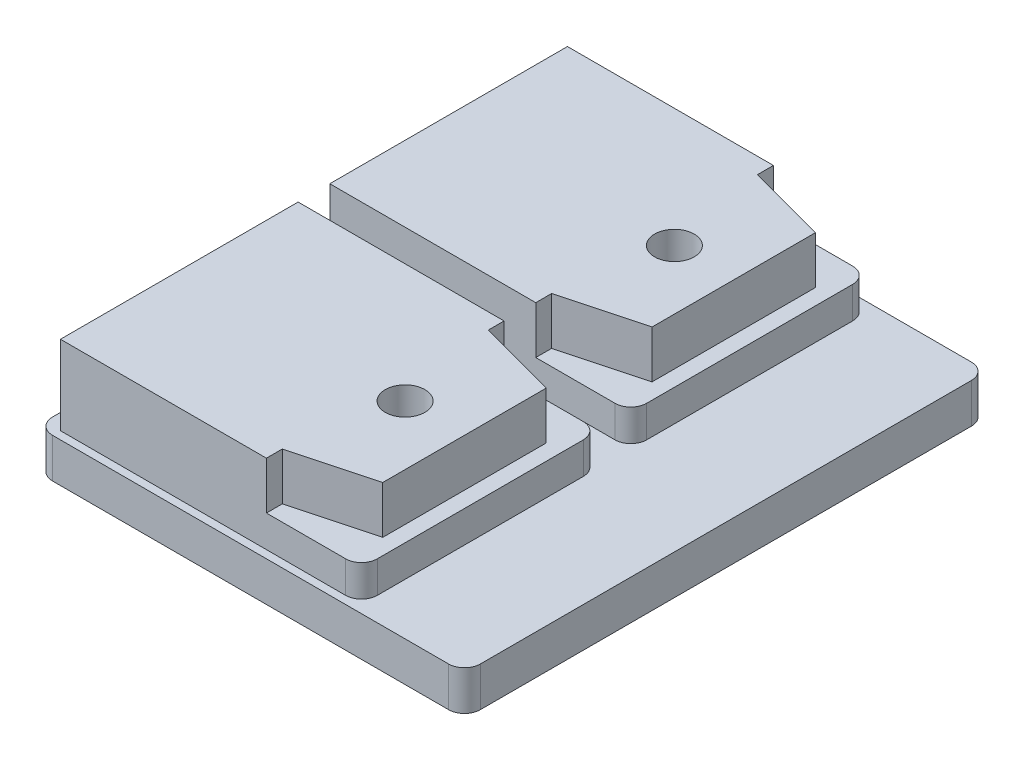
SolidWorks part; units mm, degrees
material "6061 Alloy"
ref_plane "Front Plane" through (0, 0, 0) normal (0, 0, 1) x (1, 0, 0)
ref_plane "Top Plane" through (0, 0, 0) normal (0, 1, 0) x (1, 0, 0)
ref_plane "Right Plane" through (0, 0, 0) normal (1, 0, 0) x (0, 0, -1)
other "Configuration Table"
sketch "Sketch1" plane through (0, 0, 0) normal (0, 1, 0) x (1, 0, 0)
  line L0 (13.5, 16.5) -> (-13.5, -16.5) construction
  line L1 (-13.5, 16.5) -> (13.5, 16.5)
  line L2 (-13.5, 16.5) -> (-13.5, -16.5)
  line L3 (-13.5, -16.5) -> (13.5, -16.5)
  line L4 (13.5, 16.5) -> (13.5, -16.5)
  point P4 (0, 0)
  dimension "D1" = 33
  dimension "D2" = 27
extrude "Extrude1" add sketch "Sketch1" along normal blind 2.5
fillet "Fillet1" radius 1 4 edges at (13.5, 1.25, -16.5) (-13.5, 1.25, -16.5) (-13.5, 1.25, 16.5) (13.5, 1.25, 16.5)
sketch "Sketch2" plane through (0, 2.5, 0) normal (0, 1, 0) x (-1, 0, 0)
  line L1 (12.5, 16) -> (-6.5, 16)
  line L2 (12.5, 16) -> (12.5, 1)
  line L3 (12.5, 1) -> (-6.5, 1)
  line L4 (-6.5, 16) -> (-6.5, 1)
  line L5 (13.5, -15.5) -> (13.5, 15.5) construction
  line L7 (12.5, 16.5) -> (-12.5, 16.5) construction
  dimension "D1" = 15
  dimension "D2" = 19
  dimension "D3" = 0.5
  dimension "D4" = 1
extrude "Extrude2" add sketch "Sketch2" along normal blind 5
sketch "Sketch3" plane through (0, 7.5, 0) normal (0, 1, 0) x (-1, 0, 0)
  line L0 (12.5, 16) -> (-6.5, 16) construction
  line L1 (-6.5, 1) -> (12.5, 1) construction
  line L2 (-6.5, 16) -> (-6.5, 1) construction
  line L3 (-0.5, 16) -> (-6.5, 16)
  line L4 (-6.5, 1) -> (-0.5, 1)
  line L5 (-6.5, 16) -> (-6.5, 1)
  line L6 (-0.5, 1) -> (-0.5, 2)
  line L7 (-0.5, 2) -> (-5.5, 3.3397)
  line L8 (-5.5, 3.3397) -> (-5.5, 13.6603)
  line L9 (-5.5, 13.6603) -> (-0.5, 15)
  line L10 (-0.5, 15) -> (-0.5, 16)
  line L11 (-6.5, 8.5) -> (9.5246, 8.5) construction
  point P13 (-5.5, 8.5)
  dimension "D1" = 1
  dimension "D2" = 1
  dimension "D3" = 75
  dimension "D4" = 6
extrude "Cut-Extrude1" cut sketch "Sketch3" against normal blind 3
fillet "Fillet2" radius 1 2 edges at (6.5, 3.5, 1) (6.5, 3.5, 16)
sketch "Sketch4" plane through (0, 7.5, 0) normal (0, 1, 0) x (-1, 0, 0)
  line L0 (-5.5, 3.3397) -> (-5.5, 13.6603) construction
  line L1 (-5.5, 3.3397) -> (-5.5, 13.6603) construction
  line L2 (-5.5, 8.5) -> (13.4072, 8.5) construction
  circle A0 centre (-1.75, 8.5) radius 1.25
  dimension "D1" = 2.5
  dimension "D2" = 3.75
extrude "Cut-Extrude2" cut sketch "Sketch4" against normal through all
pattern_linear "LPattern1" count 2 spacing 17 along (0, 0, -1) of "Extrude2", "Cut-Extrude1", "Cut-Extrude2", "Fillet2"
sketch "Sketch5" plane through (0, 0, 0) normal (0, -1, 0) x (1, 0, 0)
  line L1 (5.2259, 11.6531) -> (-3.0282, 11.6531)
  line L2 (5.2259, 11.6531) -> (5.2259, -11.4882)
  line L3 (5.2259, -11.4882) -> (-3.0282, -11.4882)
  line L4 (-3.0282, 11.6531) -> (-3.0282, -11.4882)
extrude "Extrude3" add sketch "Sketch5" against normal blind 2.5
